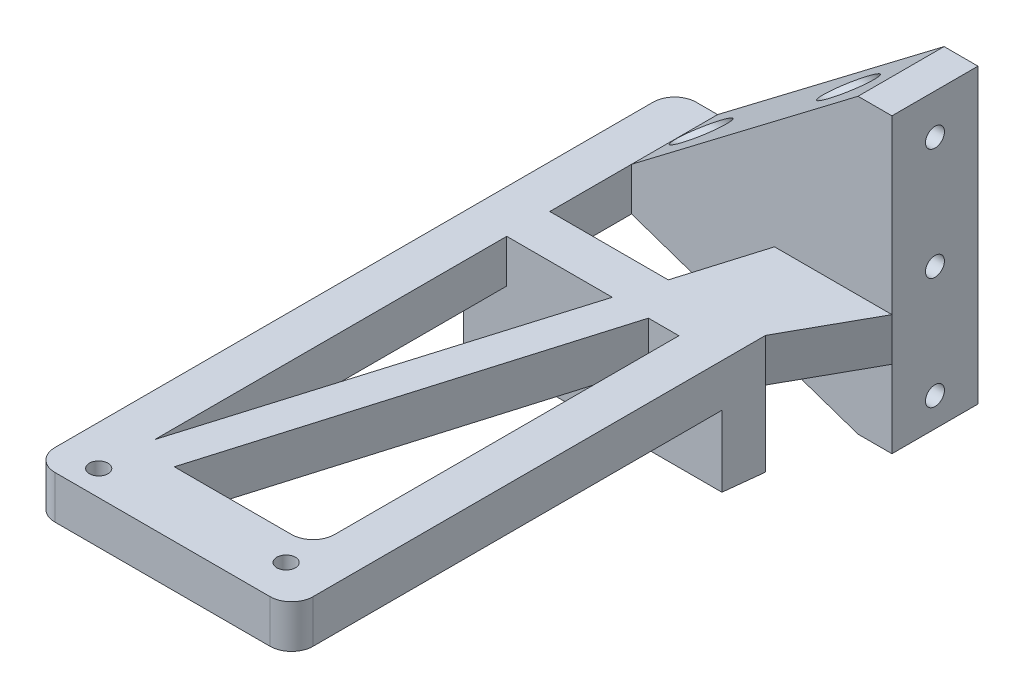
SolidWorks part; units mm, degrees
ref_plane "前视基准面" through (0, 0, 0) normal (0, 0, 1) x (1, 0, 0)
ref_plane "上视基准面" through (0, 0, 0) normal (0, 1, 0) x (1, 0, 0)
ref_plane "右视基准面" through (0, 0, 0) normal (1, 0, 0) x (0, 0, -1)
sketch "草图1" plane through (0, 0, 0) normal (0, 1, 0) x (1, 0, 0)
  line L0 (5.9312, 81.5722) -> (53.1808, 81.5722)
  line L1 (-17.3192, 81.5722) -> (5.9312, 81.5722)
  line L2 (-17.3192, 81.5722) -> (-17.3192, -67.4278)
  line L3 (-17.3192, -67.4278) -> (0.4312, -67.4278)
  line L7 (53.1808, 81.5722) -> (53.1808, 61.5722)
  line L12 (42.6808, -57.6007) -> (42.6808, -67.4278)
  line L13 (42.6808, -67.4278) -> (0.4312, -67.4278)
  line L15 (42.6808, -57.6007) -> (42.6808, 31.7573)
  line L17 (47.9308, 61.5722) -> (42.6808, 61.5722)
  line L18 (42.6808, 61.5722) -> (42.6808, 52.6895)
  line L19 (25.9063, 61.5722) -> (-7.3192, 61.5722)
  line L21 (0.4312, -52.4278) -> (32.6808, -52.4278)
  line L22 (32.6808, -52.4278) -> (32.6808, 56.5081)
  line L23 (-7.3192, 61.5722) -> (-7.3192, -49.2207)
  line L24 (25.9063, 61.5722) -> (-7.3192, -49.2207)
  line L25 (32.6808, 56.5081) -> (0.4312, -52.4278)
  line L26 (47.9308, 61.5722) -> (42.6808, 52.6895)
  line L27 (53.1808, 61.5722) -> (42.6808, 42.721)
  line L28 (42.6808, 42.721) -> (42.6808, 31.7573)
  point P0 (0, 0)
  dimension "D1" = 149
  dimension "D2" = 60
  dimension "D3" = 70.5
  dimension "D4" = 10
  dimension "D5" = 10
  dimension "D6" = 15
  dimension "D7" = 20
extrude "凸台-拉伸1" add sketch "草图1" along normal blind 10
sketch "草图4" plane through (0, 10, 0) normal (0, 1, 0) x (1, 0, 0)
  line L0 (45.3058, 81.5722) -> (45.3058, 61.5722)
  line L1 (53.1808, 81.5722) -> (-17.3192, 81.5722) construction
  line L2 (42.6808, 61.5722) -> (47.9308, 61.5722) construction
  line L3 (45.3058, 61.5722) -> (53.1808, 61.5722)
  line L4 (53.1808, 61.5722) -> (53.1808, 81.5722)
  line L5 (53.1808, 81.5722) -> (45.3058, 81.5722)
  line L7 (53.1808, 61.5722) -> (53.1808, 81.5722) construction
extrude "凸台-拉伸2" add sketch "草图4" along normal blind 40
sketch "草图5" plane through (45.3058, 0, 0) normal (-1, 0, 0) x (0, 0, 1)
  line L0 (-71.5722, 14.7) -> (-60.9452, 14.7) construction
  line L1 (-71.5722, 50) -> (-71.5722, 5.7819) construction
  line L2 (-81.5722, 50) -> (-61.5722, 50) construction
  line L3 (-81.5722, 10) -> (-61.5722, 10) construction
  circle A0 centre (-71.5722, 14.7) radius 2.2
  circle A2 centre (-71.5722, 40.7) radius 2.2
  point P4 (-71.5722, 14.7)
  dimension "D3" = 4.4
  dimension "D5" = 4.4
  dimension "D6" = 26
  dimension "D7" = 4.7
extrude "切除-拉伸1" cut sketch "草图5" against normal up to next and the other way blind 53
sketch "草图6" plane through (0, 10, 0) normal (0, 1, 0) x (1, 0, 0)
  line L0 (32.8487, -73.9107) -> (32.6808, -58.6926) construction
  line L1 (32.6808, -52.4278) -> (32.6808, 56.5081) construction
  line L2 (-25.0369, -58.6926) -> (44.4062, -58.6926) construction
  circle A0 centre (-8.0192, -61.5426) radius 2.15
  circle A1 centre (32.6808, -58.6926) radius 2.15
  dimension "D1" = 4.3
  dimension "D2" = 4.3
  dimension "D3" = 40.7
  dimension "D4" = 2.85
extrude "切除-拉伸2" cut sketch "草图6" against normal up to next
fillet "圆角1" radius 5 3 edges at (-17.3192, 5, -81.5722) (42.6808, 5, 67.4278) (-17.3192, 5, 67.4278)
fillet "圆角2" radius 5 1 edges at (32.6808, 5, 52.4278)
sketch "草图7" plane through (0, 0, 0) normal (0, -1, 0) x (1, 0, 0)
  line L0 (53.1808, -61.5722) -> (53.1808, -81.5722)
  line L1 (53.1808, -81.5722) -> (45.3058, -81.5722)
  line L2 (53.1808, -81.5722) -> (-12.3192, -81.5722) construction
  line L3 (45.3058, -81.5722) -> (45.3058, -61.5722)
  line L4 (45.3058, -61.5722) -> (53.1808, -61.5722)
  dimension "D1" = 7.875
extrude "凸台-拉伸3" add sketch "草图7" along normal blind 18
sketch "草图8" plane through (45.3058, 0, 0) normal (-1, 0, 0) x (0, 0, 1)
  line L0 (-71.5722, -18) -> (-71.5722, 20.1583) construction
  line L1 (-61.5722, -18) -> (-81.5722, -18) construction
  line L2 (-61.5722, 0) -> (-81.5722, 0) construction
  circle A0 centre (-71.5722, -11.3) radius 2.2
  dimension "D1" = 4.4
  dimension "D2" = 11.3
extrude "切除-拉伸3" cut sketch "草图8" against normal up to next
sketch "草图13" plane through (0, 0, -61.5722) normal (0, 0, 1) x (1, 0, 0)
  line L3 (45.3058, 0) -> (45.3058, -18)
  line L4 (45.3058, -18) -> (-7.3192, 0)
  line L5 (-7.3192, 0) -> (45.3058, 0)
sketch "草图14" plane through (53.1808, 0, 0) normal (1, 0, 0) x (0, 0, -1)
  circle A0 centre (71.5722, 40.7) radius 4.5
  circle A2 centre (71.5722, 14.7) radius 4.5
  circle A3 centre (71.5722, -11.3) radius 4.5
  dimension "D1" = 9
  dimension "D3" = 9
  dimension "D4" = 9
extrude "凸台-拉伸8" add sketch "草图13" against normal blind 20
sketch "草图15" plane through (0, 10, 0) normal (0, 1, 0) x (1, 0, 0)
  line L1 (45.3058, 81.5722) -> (-7.3192, 81.5722)
  line L2 (45.3058, 81.5722) -> (45.3058, 61.5722)
  line L3 (45.3058, 61.5722) -> (-7.3192, 61.5722)
  line L4 (-7.3192, 81.5722) -> (-7.3192, 61.5722)
extrude "凸台-拉伸9" add sketch "草图15" along normal blind 40
extrude "切除-拉伸8" cut sketch "草图14" against normal blind 54 from offset 7.875 offset against normal yes
sketch "草图17" plane through (0, 0, -61.5722) normal (0, 0, 1) x (1, 0, 0)
  line L1 (-7.3192, 50) -> (53.1808, 50) construction
  line L6 (-7.3192, 10) -> (-7.3192, 50)
  line L7 (-7.3192, 50) -> (45.3058, 50)
  line L8 (45.3058, 50) -> (-7.3192, 10)
  line L9 (53.1808, 50) -> (53.1808, 10) construction
  dimension "D1" = 7.875
extrude "切除-拉伸10" cut sketch "草图17" against normal blind 20
sketch "草图18" plane through (0, 10, 0) normal (0, 1, 0) x (1, 0, 0)
  line L0 (-7.3192, 32.5722) -> (17.2095, 32.5722)
  line L1 (-7.3192, 61.5722) -> (-7.3192, -49.2207) construction
  line L2 (-7.3192, -49.2207) -> (25.9063, 61.5722) construction
  line L3 (-12.3192, -67.4278) -> (37.6808, -67.4278) construction
  line L4 (-7.3192, 42.5722) -> (20.2084, 42.5722)
  line L5 (-7.3192, 42.5722) -> (-7.3192, 32.5722)
  line L6 (20.2084, 42.5722) -> (17.2095, 32.5722)
  line L7 (25.5947, 32.5722) -> (32.6808, 32.5722)
  line L8 (32.6808, 56.5081) -> (0.4312, -52.4278) construction
  line L9 (32.6808, -47.4278) -> (32.6808, 56.5081) construction
  line L10 (32.6808, 32.5722) -> (32.6808, 56.5081)
  line L11 (32.6808, 56.5081) -> (25.5947, 32.5722)
  line L12 (42.6808, 61.5722) -> (42.6808, 52.6895)
  line L13 (42.6808, 52.6895) -> (47.9308, 61.5722)
  line L14 (47.9308, 61.5722) -> (42.6808, 61.5722)
  dimension "D1" = 100
  dimension "D2" = 10
extrude "凸台-拉伸10" add sketch "草图18" against normal blind 10
sketch "草图19" plane through (0, 0, 0) normal (0, -1, 0) x (1, 0, 0)
  line L0 (0, -42.5722) -> (-29.7395, -42.5722) construction
  line L1 (20.2084, -42.5722) -> (-7.3192, -42.5722) construction
  line L2 (-2.6209, -32.5722) -> (-42.0853, -32.5722) construction
  line L3 (-7.3192, -32.5722) -> (17.2095, -32.5722) construction
  line L4 (-17.3192, -32.5722) -> (-17.3192, -42.5722)
  line L5 (-17.3192, -76.5722) -> (-17.3192, 62.4278) construction
  line L6 (-17.3192, -42.5722) -> (42.6808, -42.721)
  line L7 (42.6808, -42.721) -> (42.6808, -32.5722)
  line L8 (42.6808, 62.4278) -> (42.6808, -42.721) construction
  line L9 (42.6808, -32.5722) -> (-17.3192, -32.5722)
extrude "凸台-拉伸11" add sketch "草图19" along normal blind 17.5
sketch "草图20" plane through (-17.3192, 0, 0) normal (-1, 0, 0) x (0, 0, 1)
  line L0 (-42.5722, -17.5) -> (-32.5722, -17.5)
  line L1 (-32.5722, -17.5) -> (-32.5722, -16.5)
  line L2 (-32.5722, -17.5) -> (-32.5722, 0) construction
  line L3 (-32.5722, -16.5) -> (-42.5722, -17.5)
  dimension "D1" = 1
extrude "切除-拉伸11" cut sketch "草图20" against normal blind 64
